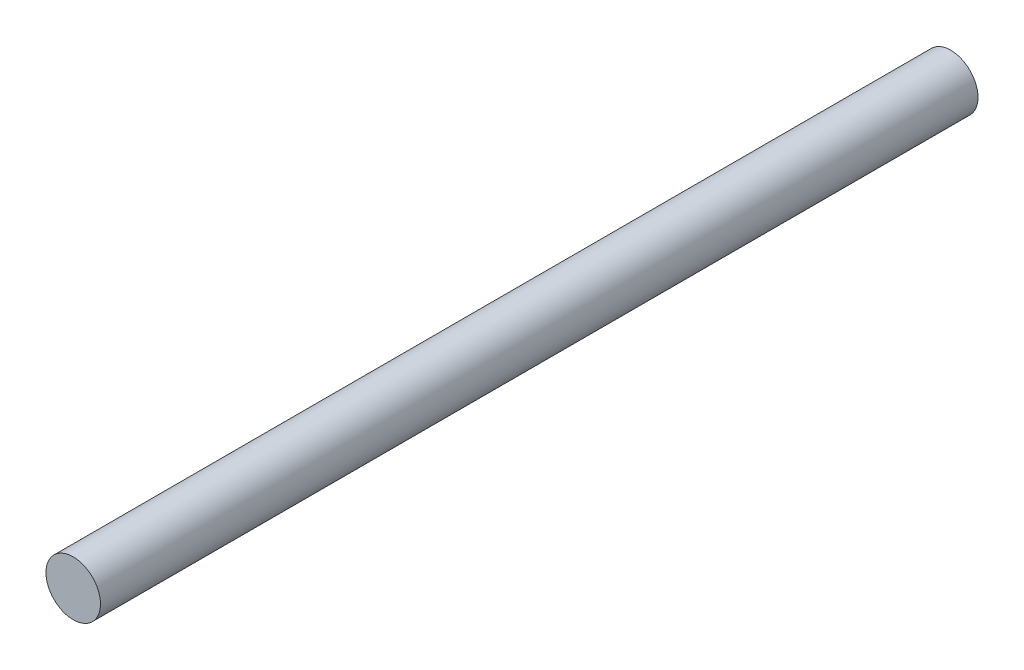
SolidWorks part; units mm, degrees
ref_plane "Plan de face" through (0, 0, 0) normal (0, 0, 1) x (1, 0, 0)
ref_plane "Plan de dessus" through (0, 0, 0) normal (0, 1, 0) x (1, 0, 0)
ref_plane "Plan de droite" through (0, 0, 0) normal (1, 0, 0) x (0, 0, -1)
sketch "Esquisse1" plane through (0, 0, 0) normal (0, 0, 1) x (1, 0, 0)
  circle A0 centre (0, 0) radius 2.95
  dimension "D1" = 5.9
extrude "Boss.-Extru.1" add sketch "Esquisse1" along normal blind 95
